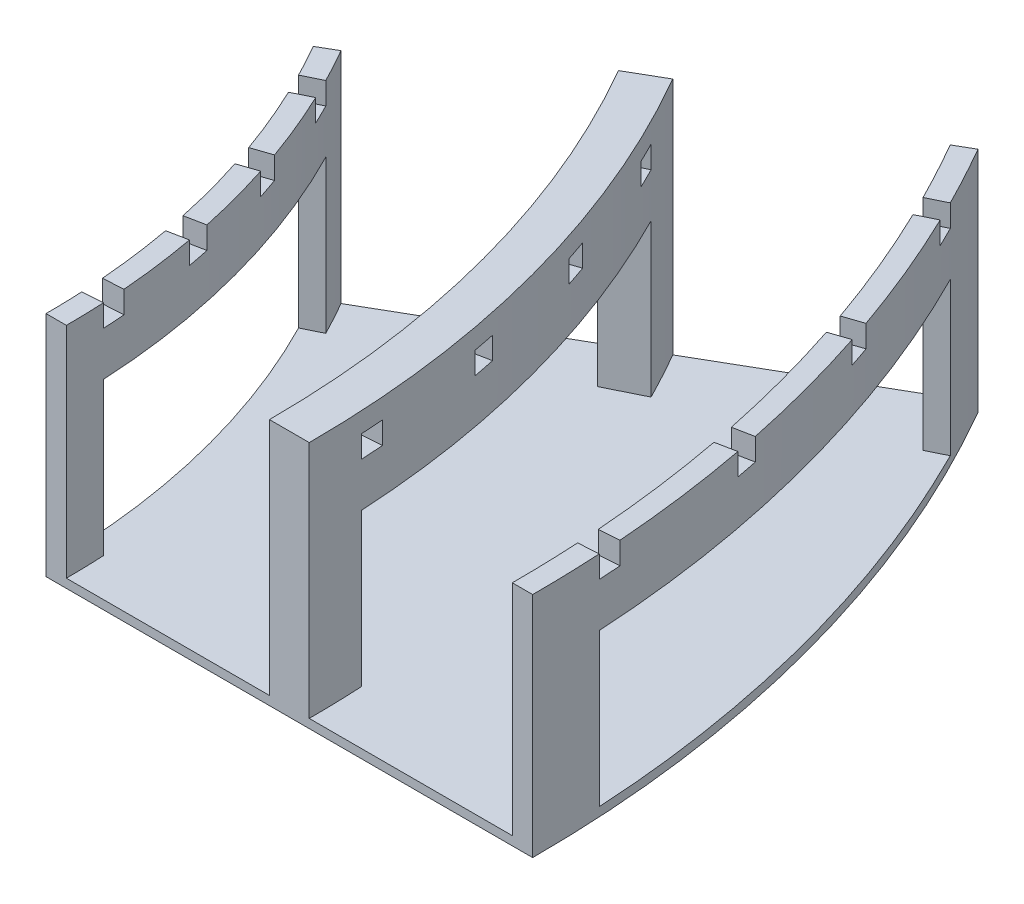
SolidWorks part; units mm, degrees
ref_plane "Ebene vorne" through (0, 0, 0) normal (0, 0, 1) x (1, 0, 0)
ref_plane "Ebene oben" through (0, 0, 0) normal (0, 1, 0) x (1, 0, 0)
ref_plane "Ebene rechts" through (0, 0, 0) normal (1, 0, 0) x (0, 0, -1)
sketch "Skizze1" plane through (0, 0, 0) normal (0, 1, 0) x (1, 0, 0)
  line L0 (165, 0) -> (169.6, 0) construction
  line L1 (146.8779, 84.8) -> (142.8942, 82.5) construction
  line L2 (0, 0) -> (146.8779, 84.8) construction
  line L3 (270.4, 0) -> (275, 0) construction
  line L4 (238.157, 137.5) -> (234.1733, 135.2) construction
  line L5 (169.6, 0) -> (270.4, 0) construction
  line L6 (146.8779, 84.8) -> (234.1733, 135.2) construction
  line L7 (194.4227, 112.25) -> (186.6285, 107.75) construction
  line L8 (224.5, 0) -> (215.5, 0) construction
  line L9 (194.4227, 112.25) -> (190.5256, 110) construction
  line L10 (165, 0) -> (169.6, 0)
  line L11 (142.8942, 82.5) -> (146.8779, 84.8)
  line L13 (215.5, 0) -> (224.5, 0)
  line L15 (194.4227, 112.25) -> (186.6285, 107.75)
  line L16 (234.1733, 135.2) -> (238.157, 137.5)
  line L17 (270.4, 0) -> (275, 0)
  arc A0 (165, 0) -> (142.8942, 82.5) centre (0, 0) ccw
  arc A1 (169.6, 0) -> (146.8779, 84.8) centre (0, 0) ccw
  arc A2 (270.4, 0) -> (234.1733, 135.2) centre (0, 0) ccw
  arc A3 (275, 0) -> (238.157, 137.5) centre (0, 0) ccw
  arc A4 (220, 0) -> (190.5256, 110) centre (0, 0) ccw construction
  arc A5 (215.5, 0) -> (186.6285, 107.75) centre (0, 0) ccw
  arc A6 (224.5, 0) -> (194.4227, 112.25) centre (0, 0) ccw
  dimension "D1" = 165
  dimension "D4" = 275
  dimension "D2" = 4.6
  dimension "D3" = 30
  dimension "D5" = 4.5
  dimension "D6" = 4.5
extrude "Aufsatz-Linear austragen1" add sketch "Skizze1" along normal blind 51.5
sketch "Skizze2" plane through (0, 51.5, 0) normal (0, 1, 0) x (1, 0, 0)
  line L0 (0, 0) -> (275, 0) construction
  line L1 (0, 0) -> (274.4112, 17.9859) construction
  line L2 (164.4643, 13.2849) -> (274.2364, 20.4798)
  line L3 (164.7913, 8.2956) -> (274.5634, 15.4905)
  line L4 (161.3233, 34.6382) -> (269.2171, 56.0996)
  line L5 (162.2987, 29.7342) -> (270.1925, 51.1957)
  line L6 (0, 0) -> (161.8296, 32.1899) construction
  line L7 (157.0291, 50.6641) -> (261.1986, 86.0249)
  line L8 (155.4219, 55.3987) -> (259.5914, 90.7595)
  line L9 (149.0727, 70.7271) -> (247.7355, 119.3822)
  line L10 (146.8613, 75.2114) -> (245.5241, 123.8665)
  line L21 (0, 0) -> (156.2435, 53.0375) construction
  line L22 (0, 0) -> (147.984, 72.9776) construction
  arc A0 (275, 0) -> (238.157, 137.5) centre (0, 0) ccw construction
  arc A1 (164.7913, 8.2956) -> (164.4643, 13.2849) centre (0, 0) ccw
  arc A2 (165, 0) -> (142.8942, 82.5) centre (0, 0) ccw construction
  arc A3 (274.5634, 15.4905) -> (274.2364, 20.4798) centre (0, 0) ccw
  arc A4 (162.2987, 29.7342) -> (161.3233, 34.6382) centre (0, 0) ccw
  arc A5 (270.1925, 51.1957) -> (269.2171, 56.0996) centre (0, 0) ccw
  arc A6 (157.0291, 50.6641) -> (155.4219, 55.3987) centre (0, 0) ccw
  arc A7 (261.1986, 86.0249) -> (259.5914, 90.7595) centre (0, 0) ccw
  arc A8 (149.0727, 70.7271) -> (146.8613, 75.2114) centre (0, 0) ccw
  arc A9 (247.7355, 119.3822) -> (245.5241, 123.8665) centre (0, 0) ccw
  point P22 (0, 0)
  point P52 (0, 0)
  dimension "D1" = 5
  dimension "D2" = 2.5
  dimension "D3" = 3.75
  dimension "D5" = 7.5
  dimension "D7" = 7.5
  dimension "D6" = 7.5
  dimension "D12" = 5
  dimension "D13" = 5
  dimension "D4" = 2
extrude "Schnitt-Linear austragen1" cut sketch "Skizze2" against normal blind 5
sketch "Skizze4" plane through (0, 0, 0) normal (0, -1, 0) x (1, 0, 0)
  line L0 (165, 0) -> (275, 0)
  line L1 (142.8942, -82.5) -> (238.157, -137.5)
  line L2 (194.4227, -112.25) -> (186.6285, -107.75) construction
  line L3 (215.5, 0) -> (224.5, 0) construction
  arc A0 (238.157, -137.5) -> (275, 0) centre (0, 0) ccw
  arc A1 (142.8942, -82.5) -> (165, 0) centre (0, 0) ccw
  arc A2 (142.8942, -82.5) -> (165, 0) centre (0, 0) ccw construction
  arc A3 (238.157, -137.5) -> (275, 0) centre (0, 0) ccw construction
extrude "Aufsatz-Linear austragen2" add sketch "Skizze4" against normal blind 2
sketch "Skizze5" plane through (0, 51.5, 0) normal (0, 1, 0) x (1, 0, 0)
  line L1 (164.7913, 8.2956) -> (274.5634, 15.4905)
  line L3 (146.8613, 75.2114) -> (245.5241, 123.8665)
  arc A12 (164.7913, 8.2956) -> (146.8613, 75.2114) centre (0, 0) ccw
  arc A14 (274.5634, 15.4905) -> (245.5241, 123.8665) centre (0, 0) ccw
extrude "Schnitt-Linear austragen2" cut sketch "Skizze5" against normal up to surface (34.5 mm away) from offset 15 up to face at (182.8203, 2, -48.9866) offset against normal yes
sketch "Skizze6" plane through (0, 51.5, 0) normal (0, 1, 0) x (1, 0, 0)
  line L0 (186.6285, 107.75) -> (194.4227, 112.25)
  line L1 (215.5, 0) -> (224.5, 0)
  arc A0 (215.5, 0) -> (186.6285, 107.75) centre (0, 0) ccw
  arc A1 (224.5, 0) -> (194.4227, 112.25) centre (0, 0) ccw
extrude "Aufsatz-Linear austragen3" add sketch "Skizze6" along normal blind 4.5
equation "\"D6@Skizze1\"=\"D5@Skizze1\""
equation "\"D2@Skizze2\"=\"D1@Skizze2\"/2"
